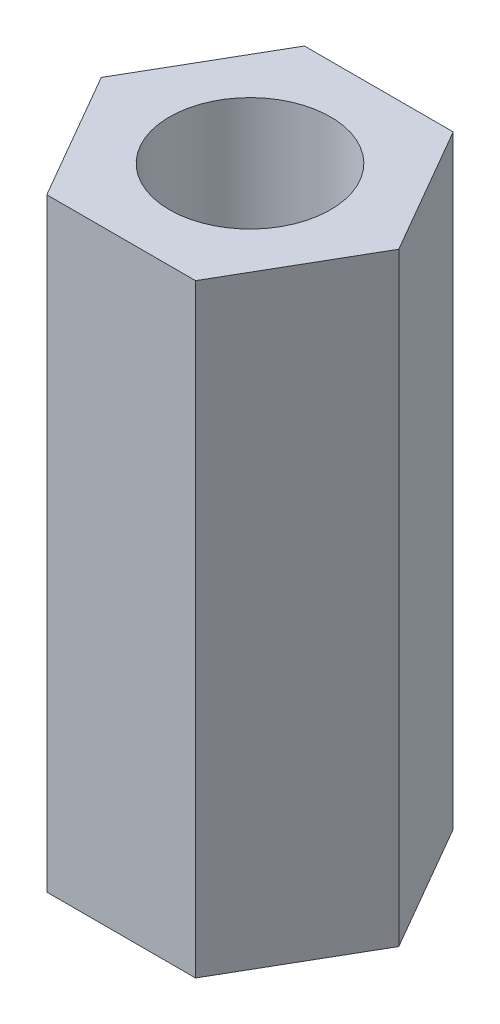
SolidWorks part; units mm, degrees
ref_plane "Front Plane" through (0, 0, 0) normal (0, 0, 1) x (1, 0, 0)
ref_plane "Top Plane" through (0, 0, 0) normal (0, 1, 0) x (1, 0, 0)
ref_plane "Right Plane" through (0, 0, 0) normal (1, 0, 0) x (0, 0, -1)
sketch "Sketch1" plane through (0, 0, 0) normal (0, 1, 0) x (1, 0, 0)
  line L1 (2.765, 3.0918) -> (-0.93, 9.4918)
  line L2 (-0.93, 9.4918) -> (-8.3201, 9.4918)
  line L3 (-8.3201, 9.4918) -> (-12.0152, 3.0918)
  line L4 (-12.0152, 3.0918) -> (-8.3201, -3.3082)
  line L5 (-8.3201, -3.3082) -> (-0.93, -3.3082)
  line L6 (-0.93, -3.3082) -> (2.765, 3.0918)
  circle A0 centre (-4.6251, 3.0918) radius 6.4 construction
  circle A1 centre (-4.6251, 3.0918) radius 4
  dimension "D2" = 8
  dimension "D1" = 12.8
extrude "Boss-Extrude1" add sketch "Sketch1" along normal blind 30
